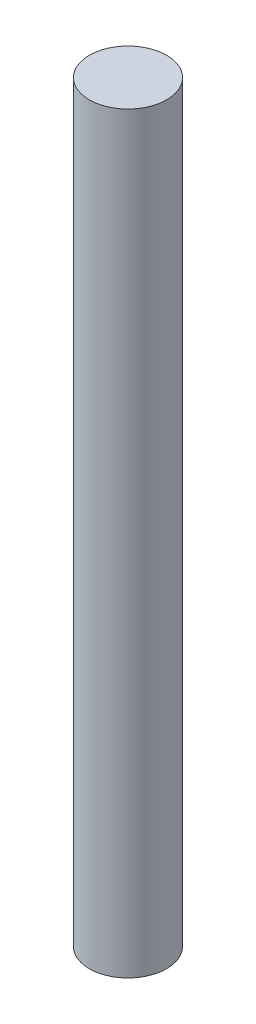
SolidWorks part; units mm, degrees
ref_plane "Front Plane" through (0, 0, 0) normal (0, 0, 1) x (1, 0, 0)
ref_plane "Top Plane" through (0, 0, 0) normal (0, 1, 0) x (1, 0, 0)
ref_plane "Right Plane" through (0, 0, 0) normal (1, 0, 0) x (0, 0, -1)
sketch "Sketch1" plane through (0, 0, 0) normal (0, 1, 0) x (1, 0, 0)
  circle A0 centre (0, 0) radius 2.5
  dimension "D1" = 5
extrude "Boss-Extrude1" add sketch "Sketch1" along normal blind 48.7
